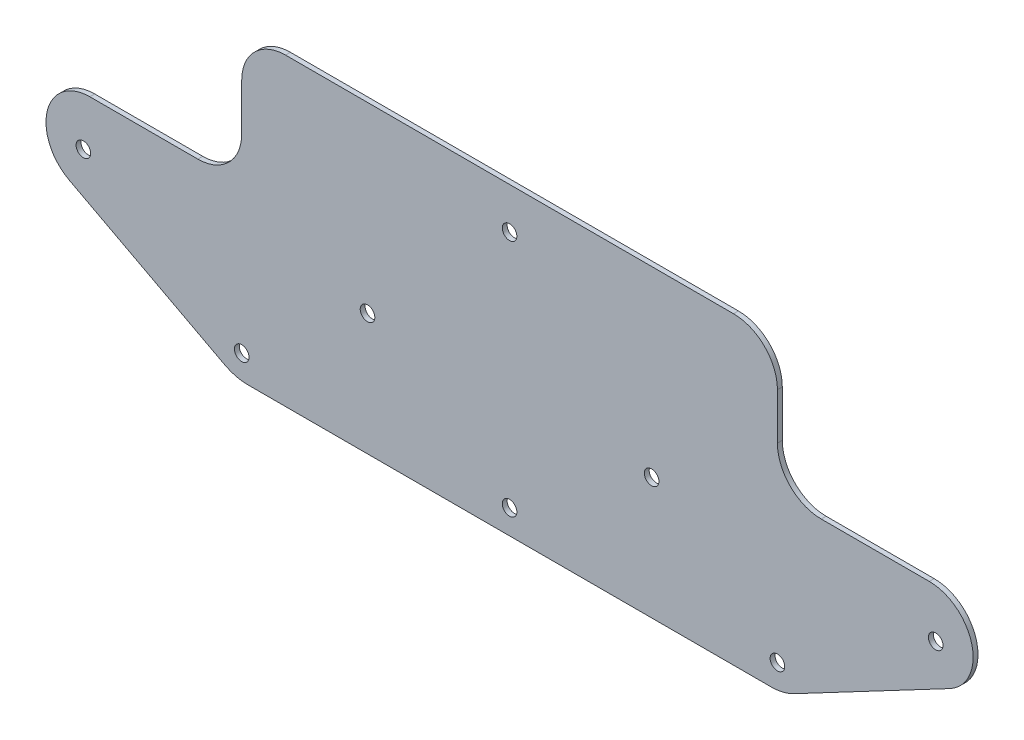
SolidWorks part; units mm, degrees
ref_plane "Plan de face" through (0, 0, 0) normal (0, 0, 1) x (1, 0, 0)
ref_plane "Plan de dessus" through (0, 0, 0) normal (0, 1, 0) x (1, 0, 0)
ref_plane "Plan de droite" through (0, 0, 0) normal (1, 0, 0) x (0, 0, -1)
sketch "Esquisse1" plane through (0, 0, 0) normal (0, 0, 1) x (1, 0, 0)
  line L0 (0, 0) -> (0, 122.747) construction
  line L1 (-175, -20) -> (175, -20) construction
  line L2 (-175, -20) -> (-175, 20) construction
  line L3 (-175, 20) -> (175, 20) construction
  line L4 (175, -20) -> (175, 20) construction
  line L5 (-175, -20) -> (175, 20) construction
  line L6 (-175, 20) -> (175, -20) construction
  line L7 (-1220, 0) -> (-110, 0) construction
  line L8 (-244.959, 40) -> (-110, 40)
  line L9 (110, 40) -> (244.959, 40)
  line L10 (110, 0) -> (110, -20) construction
  line L11 (110, -20) -> (-110, -20) construction
  line L12 (-110, 0) -> (-110, -20) construction
  line L13 (110, 0) -> (-110, -20) construction
  line L14 (110, -20) -> (-110, 0) construction
  line L15 (-244.959, 40) -> (-112.4795, -30)
  line L16 (-112.4795, -30) -> (112.4795, -30)
  line L17 (244.959, 40) -> (112.4795, -30)
  line L18 (-175, 20) -> (-58.3333, 20) construction
  line L19 (-58.3333, 20) -> (58.3333, 20) construction
  line L20 (58.3333, 20) -> (175, 20) construction
  line L21 (110, 0) -> (193.5165, 0) construction
  line L22 (110, 95) -> (-110, 95)
  line L23 (110, 95) -> (110, 40)
  line L25 (-110, 95) -> (-110, 40)
  line L26 (110, 95) -> (-110, 0) construction
  line L27 (110, 0) -> (-110, 95) construction
  circle A0 centre (-175, 20) radius 3
  circle A1 centre (-110, -20) radius 3
  circle A2 centre (110, -20) radius 3
  circle A3 centre (175, 20) radius 3
  circle A4 centre (0, -20) radius 3
  circle A5 centre (-58.3333, 20) radius 3
  circle A6 centre (58.3333, 20) radius 3
  circle A7 centre (0, 78.03) radius 3
  point P0 (0, 0)
  point P8 (0, -10)
  point P20 (0, 47.5)
  point P21 (0, -30)
  point P31 (0, 47.5)
  dimension "D8" = 6
  dimension "D10" = 58.03
  dimension "D1" = 350
  dimension "D2" = 40
  dimension "D3" = 220
  dimension "D4" = 20
  dimension "D5" = 15
  dimension "D6" = 10
  dimension "D7" = 10
  dimension "D9" = 55
extrude "Boss.-Extru.1" add sketch "Esquisse1" along normal blind 2
fillet "Congé1" radius 18 6 edges at (-244.959, 40, 1) (-110, 40, 1) (-110, 95, 1) (110, 95, 1) (110, 40, 1) (244.959, 40, 1)
fillet "Congé2" radius 20 2 edges at (-112.4795, -30, 1) (112.4795, -30, 1)
